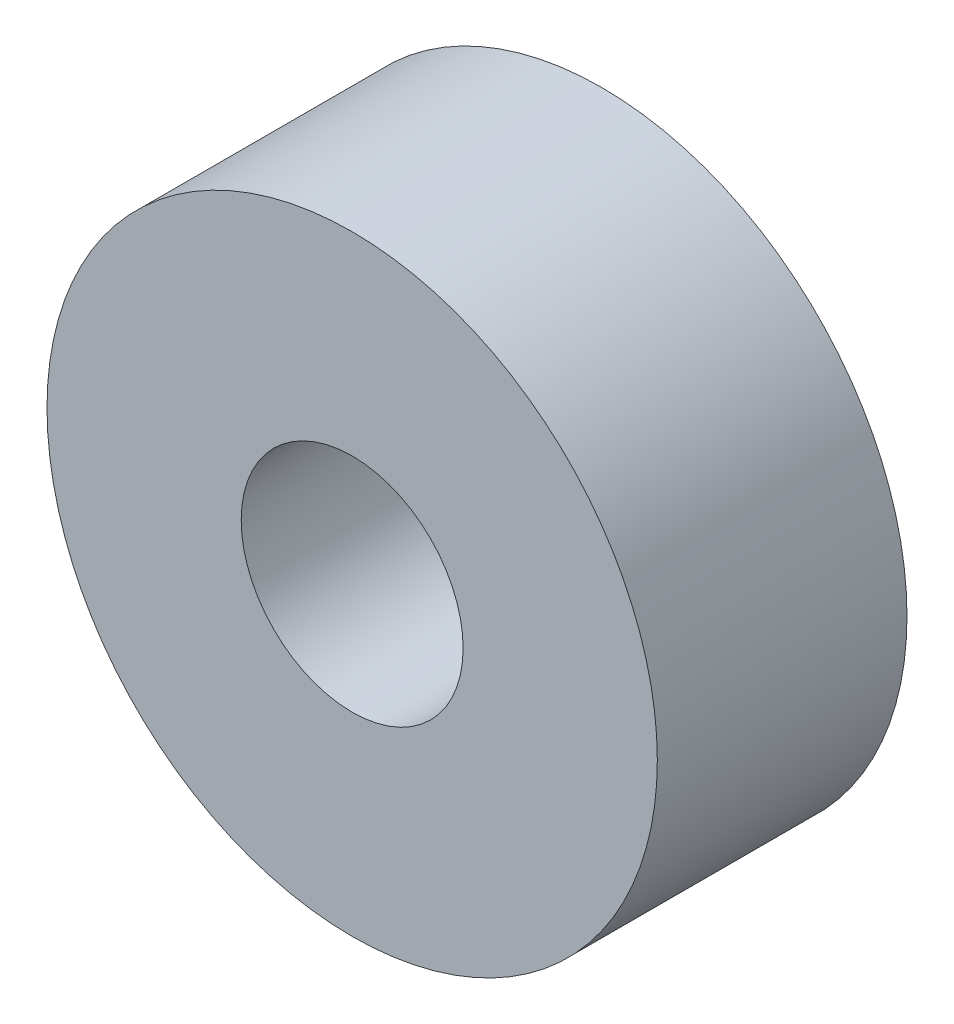
SolidWorks part; units mm, degrees
ref_plane "前视基准面" through (0, 0, 0) normal (0, 0, 1) x (1, 0, 0)
ref_plane "上视基准面" through (0, 0, 0) normal (0, 1, 0) x (1, 0, 0)
ref_plane "右视基准面" through (0, 0, 0) normal (1, 0, 0) x (0, 0, -1)
other "Configuration Table"
sketch "草图1" plane through (0, 0, 0) normal (0, 0, 1) x (1, 0, 0)
  circle A0 centre (0, 0) radius 22
  circle A1 centre (0, 0) radius 8
extrude "凸台-拉伸1" add sketch "草图1" along normal blind 18
